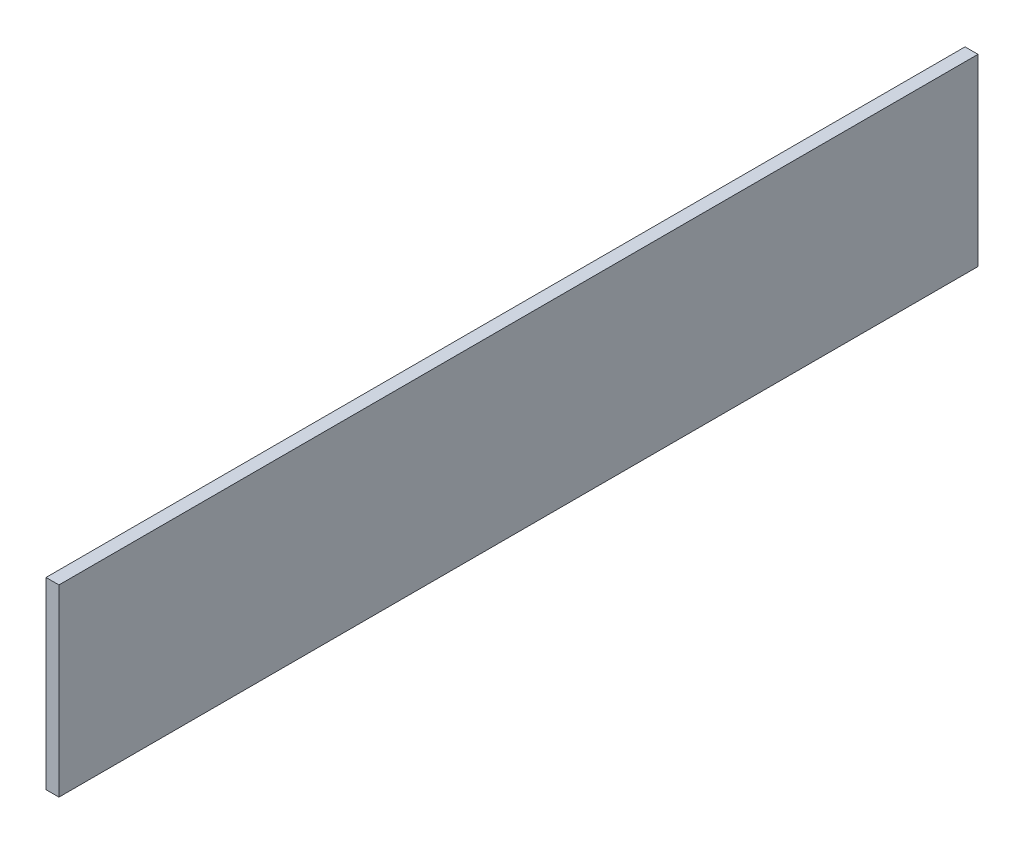
SolidWorks part; units mm, degrees
ref_plane "Alzado" through (0, 0, 0) normal (0, 0, 1) x (1, 0, 0)
ref_plane "Planta" through (0, 0, 0) normal (0, 1, 0) x (1, 0, 0)
ref_plane "Vista lateral" through (0, 0, 0) normal (1, 0, 0) x (0, 0, -1)
sketch "Croquis1" plane through (0, 0, 0) normal (1, 0, 0) x (0, 0, -1)
  line L1 (-88.3307, -18.7283) -> (266.6693, -18.7283)
  line L2 (-88.3307, -18.7283) -> (-88.3307, 52.2717)
  line L3 (-88.3307, 52.2717) -> (266.6693, 52.2717)
  line L4 (266.6693, -18.7283) -> (266.6693, 52.2717)
  dimension "D1" = 71
  dimension "D2" = 355
extrude "Saliente-Extruir1" add sketch "Croquis1" along normal blind 5
